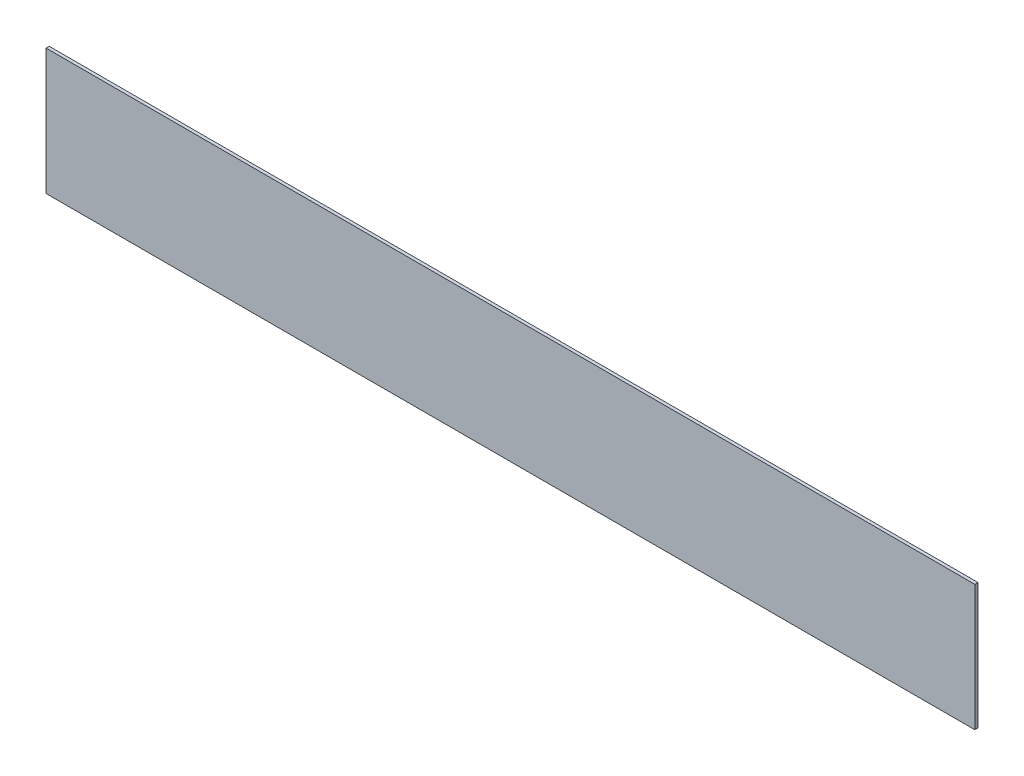
SolidWorks part; units mm, degrees
ref_plane "Front Plane" through (0, 0, 0) normal (0, 0, 1) x (1, 0, 0)
ref_plane "Top Plane" through (0, 0, 0) normal (0, 1, 0) x (1, 0, 0)
ref_plane "Right Plane" through (0, 0, 0) normal (1, 0, 0) x (0, 0, -1)
sketch "Sketch1" plane through (0, 0, 0) normal (0, 0, 1) x (1, 0, 0)
  line L1 (0, 0) -> (590, 0)
  line L2 (0, 0) -> (0, -80)
  line L3 (0, -80) -> (590, -80)
  line L4 (590, 0) -> (590, -80)
  dimension "D1" = 590
  dimension "D2" = 80
extrude "Boss-Extrude1" add sketch "Sketch1" along normal blind 2
